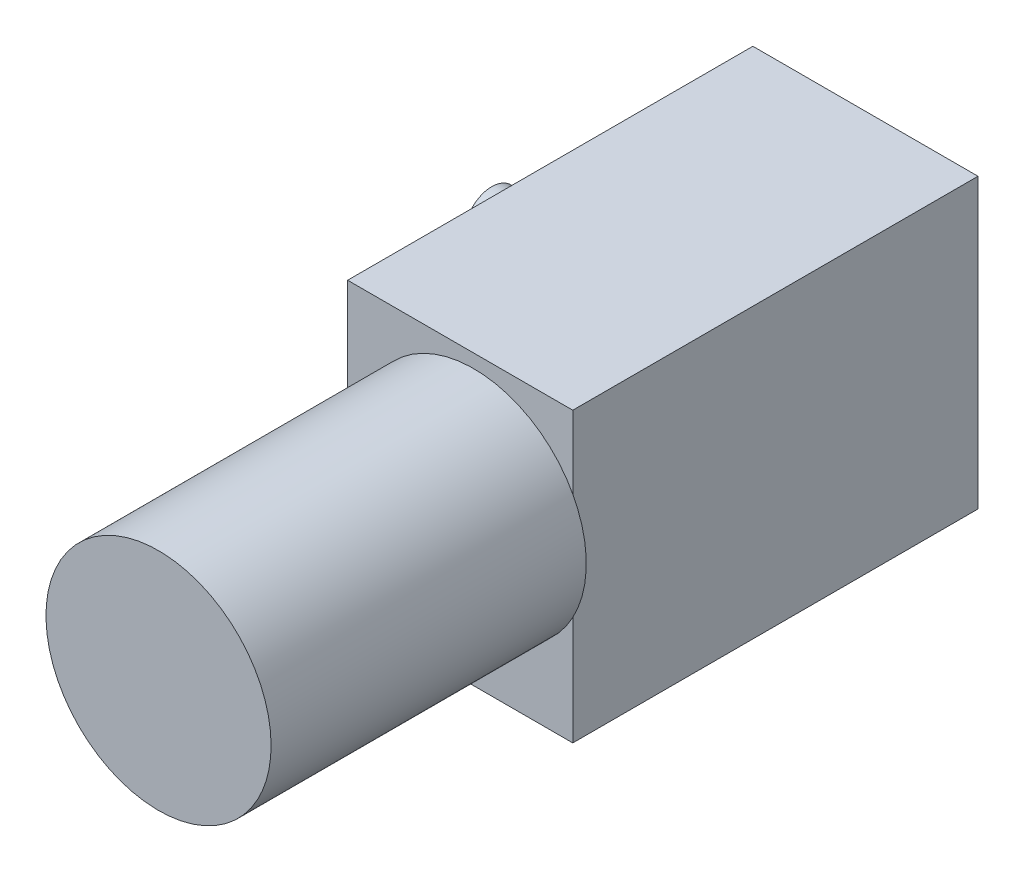
SolidWorks part; units mm, degrees
material "AISI 1020"
ref_plane "Front Plane" through (0, 0, 0) normal (0, 0, 1) x (1, 0, 0)
ref_plane "Top Plane" through (0, 0, 0) normal (0, 1, 0) x (1, 0, 0)
ref_plane "Right Plane" through (0, 0, 0) normal (1, 0, 0) x (0, 0, -1)
sketch "Sketch1" plane through (0, 0, 0) normal (1, 0, 0) x (0, 0, -1)
  line L1 (-28.1772, 7.2044) -> (16.8228, 7.2044)
  line L2 (-28.1772, 7.2044) -> (-28.1772, -24.7956)
  line L3 (-28.1772, -24.7956) -> (16.8228, -24.7956)
  line L4 (16.8228, 7.2044) -> (16.8228, -24.7956)
  dimension "D1" = 45
  dimension "D2" = 32
extrude "Boss-Extrude1" add sketch "Sketch1" along normal blind 25
sketch "Sketch2" plane through (0, 0, 28.1772) normal (0, 0, 1) x (1, 0, 0)
  line L0 (25, 7.2044) -> (25, -24.7956) construction
  line L1 (25, 7.2044) -> (0, 7.2044) construction
  circle A0 centre (14, -6.7956) radius 12.5
  dimension "D1" = 11
  dimension "D2" = 14
extrude "Boss-Extrude2" add sketch "Sketch2" along normal blind 35
sketch "Sketch3" plane through (0, 0, 0) normal (-1, 0, 0) x (0, 0, 1)
  line L0 (-16.8228, -24.7956) -> (-16.8228, 7.2044) construction
  line L1 (-16.8228, 7.2044) -> (28.1772, 7.2044) construction
  circle A0 centre (-1.8228, -8.7956) radius 3
  point P6 (22.1772, 0.2044)
  point P7 (22.1772, -17.7956)
  point P9 (-10.8228, 0.2044)
  point P11 (-10.8228, -17.7956)
  dimension "D1" = 15
  dimension "D2" = 16
extrude "Boss-Extrude3" add sketch "Sketch3" along normal blind 14
sketch "Sketch4" plane through (0, 0, 0) normal (-1, 0, 0) x (0, 0, 1)
  line L0 (-10.8228, 0.2044) -> (-10.8228, -17.7956) construction
  line L1 (-10.8228, -17.7956) -> (22.1772, -17.7956) construction
  line L2 (22.1772, -17.7956) -> (22.1772, 0.2044) construction
  line L3 (22.1772, 0.2044) -> (-10.8228, 0.2044) construction
  line L4 (22.1772, 0.2044) -> (22.1772, -1.2956)
  circle A2 centre (-10.8228, 0.2044) radius 1.5
  circle A3 centre (22.1772, 0.2044) radius 1.5
  circle A4 centre (22.1772, -17.7956) radius 1.5
  circle A5 centre (-10.8228, -17.7956) radius 1.5
  circle A6 centre (-1.8228, -8.7956) radius 3 construction
  dimension "D5" = 3
  dimension "D6" = 3
  dimension "D7" = 3
  dimension "D8" = 3
  dimension "D1" = 9
  dimension "D2" = 18
  dimension "D3" = 9
  dimension "D4" = 33
extrude "Cut-Extrude1" cut sketch "Sketch4" against normal blind 5
